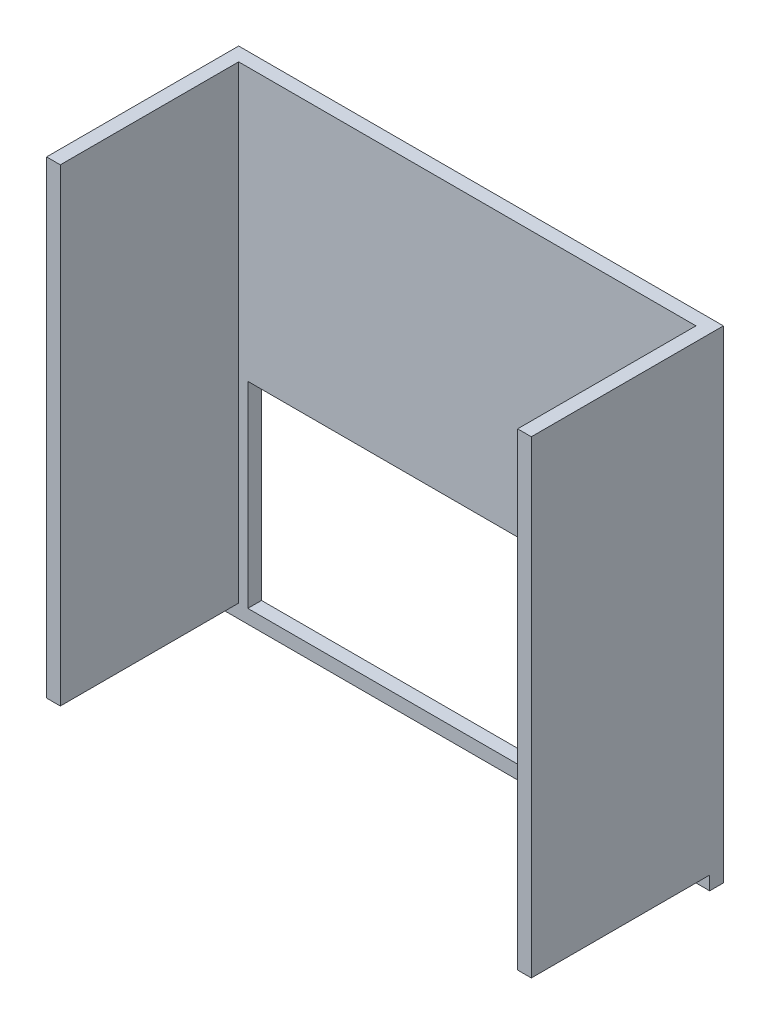
SolidWorks part; units mm, degrees
ref_plane "Front Plane" through (0, 0, 0) normal (0, 0, 1) x (1, 0, 0)
ref_plane "Top Plane" through (0, 0, 0) normal (0, 1, 0) x (1, 0, 0)
ref_plane "Right Plane" through (0, 0, 0) normal (1, 0, 0) x (0, 0, -1)
sketch "Sketch1" plane through (0, 0, 0) normal (0, 1, 0) x (1, 0, 0)
  line L1 (-50, -38.75) -> (50, -38.75)
  line L2 (-50, -38.75) -> (-50, 38.75)
  line L3 (-50, 38.75) -> (50, 38.75)
  line L4 (50, -38.75) -> (50, 38.75)
  line L5 (-50, -38.75) -> (50, 38.75) construction
  line L6 (-50, 38.75) -> (50, -38.75) construction
  point P0 (0, 0)
  dimension "D1" = 77.5
  dimension "D2" = 100
extrude "Boss-Extrude1" add sketch "Sketch1" along normal blind 3 contours L3 L4 L1 L2
sketch "Sketch2" plane through (0, 3, 0) normal (0, 1, 0) x (1, 0, 0)
  line L4 (-50, -38.75) -> (50, -38.75) construction
  line L5 (50, -38.75) -> (50, 38.75) construction
  line L6 (-50, 38.75) -> (50, 38.75) construction
  line L7 (-50, -38.75) -> (-50, 38.75) construction
  line L8 (-53, 41.75) -> (-53, -41.75)
  line L9 (-53, -41.75) -> (53, -41.75)
  line L10 (53, -41.75) -> (53, 41.75)
  line L11 (53, 41.75) -> (-53, 41.75)
  line L12 (-53, 41.75) -> (-53, -41.75)
  line L13 (-53, -41.75) -> (53, -41.75)
  line L14 (53, -41.75) -> (53, 41.75)
  line L15 (53, 41.75) -> (-53, 41.75)
  line L16 (-50, -38.75) -> (50, -38.75)
  line L17 (50, -38.75) -> (50, 38.75)
  line L18 (-50, 38.75) -> (50, 38.75)
  line L19 (-50, -38.75) -> (-50, 38.75)
  dimension "D1" = 3
extrude "Boss-Extrude2" add sketch "Sketch2" along normal blind 102.5 and the other way blind 3
sketch "Sketch3" plane through (0, 0, 41.75) normal (0, 0, -1) x (-1, 0, 0)
  line L0 (-53, 0) -> (53, 0) construction
  line L1 (-53, 105.5) -> (53, 105.5)
  line L2 (-53, 105.5) -> (-53, 0)
  line L3 (-53, 0) -> (53, 0)
  line L4 (53, 105.5) -> (53, 0)
  line L5 (-53, 105.5) -> (53, 105.5) construction
  line L9 (-53, 0) -> (-53, 105.5) construction
  point P6 (0, 105.5)
extrude "Cut-Extrude1" cut sketch "Sketch3" along normal blind 41.5
sketch "Sketch6" plane through (0, 0, -41.75) normal (0, 0, -1) x (-1, 0, 0)
  line L0 (53, 0) -> (53, 105.5) construction
  line L1 (48, 3) -> (-48, 3)
  line L2 (48, 3) -> (48, 46)
  line L3 (48, 46) -> (-48, 46)
  line L4 (-48, 3) -> (-48, 46)
  line L6 (-53, 0) -> (-53, 105.5) construction
  line L7 (-53, 0) -> (53, 0) construction
  dimension "D1" = 5
  dimension "D2" = 5
  dimension "D3" = 3
  dimension "D4" = 43
extrude "Cut-Extrude3" cut sketch "Sketch6" against normal up to next
sketch "Sketch7" plane through (0, 0, 0.25) normal (0, 0, 1) x (1, 0, 0)
  line L0 (53, 0) -> (-53, 0) construction
  line L1 (-53, 3) -> (53, 3)
  line L2 (-53, 3) -> (-53, 0)
  line L3 (-53, 0) -> (53, 0)
  line L4 (53, 3) -> (53, 0)
  line L6 (53, 105.5) -> (53, 0) construction
  line L7 (-53, 0) -> (-53, 105.5) construction
extrude "Cut-Extrude4" cut sketch "Sketch7" against normal up to surface (39 mm away) up to face at (0, 39.375, -38.75)
